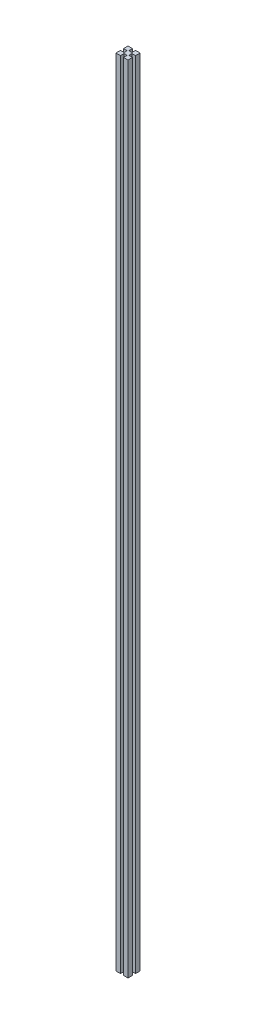
SolidWorks part; units mm, degrees
ref_plane "Front Plane" through (0, 0, 0) normal (0, 0, 1) x (1, 0, 0)
ref_plane "Top Plane" through (0, 0, 0) normal (0, 1, 0) x (1, 0, 0)
ref_plane "Right Plane" through (0, 0, 0) normal (1, 0, 0) x (0, 0, -1)
sketch "Sketch1" plane through (0, 0, 0) normal (0, 1, 0) x (1, 0, 0)
  line L1 (-10, -10) -> (10, -10)
  line L2 (-10, -10) -> (-10, 10)
  line L3 (-10, 10) -> (10, 10)
  line L4 (10, -10) -> (10, 10)
  line L5 (-10, -10) -> (10, 10) construction
  line L6 (-10, 10) -> (10, -10) construction
  point P0 (0, 0)
  dimension "D1" = 20
  dimension "D2" = 20
extrude "Boss-Extrude1" add sketch "Sketch1" along normal blind 656.463 and the other way blind 656.463
sketch "Sketch2" plane through (0, 0, 0) normal (0, 1, 0) x (1, 0, 0)
  line L0 (-2.5, 4) -> (2.5, 4)
  line L1 (-2.5, 4) -> (-2.5, 16)
  line L2 (-2.5, 16) -> (2.5, 16)
  line L3 (2.5, 4) -> (2.5, 16)
  line L4 (-2.5, 4) -> (2.5, 16) construction
  line L5 (-2.5, 16) -> (2.5, 4) construction
  line L6 (4, 2.5) -> (16, 2.5)
  line L7 (4, 2.5) -> (4, -2.5)
  line L8 (4, -2.5) -> (16, -2.5)
  line L9 (16, 2.5) -> (16, -2.5)
  line L10 (4, 2.5) -> (16, -2.5) construction
  line L11 (4, -2.5) -> (16, 2.5) construction
  line L12 (-10, 10) -> (10, -10) construction
  line L13 (-16, 2.5) -> (-4, -2.5) construction
  line L14 (-4, 2.5) -> (-16, -2.5) construction
  line L15 (-4, -2.5) -> (-16, -2.5)
  line L16 (-16, 2.5) -> (-16, -2.5)
  line L17 (-4, 2.5) -> (-16, 2.5)
  line L18 (-4, 2.5) -> (-4, -2.5)
  line L19 (2.5, -4) -> (2.5, -16)
  line L20 (2.5, -4) -> (-2.5, -16) construction
  line L21 (-2.5, -4) -> (2.5, -16) construction
  line L22 (-2.5, -16) -> (2.5, -16)
  line L23 (-2.5, -4) -> (2.5, -4)
  line L24 (-2.5, -4) -> (-2.5, -16)
  line L25 (-10, 10) -> (-10, -10) construction
  line L26 (10, -10) -> (10, 10) construction
  line L27 (-10, -10) -> (10, -10) construction
  line L28 (10, 10) -> (-10, 10) construction
  point P0 (0, 10)
  point P5 (10, 0)
  point P16 (-10, 0)
  point P21 (0, -10)
  dimension "D1" = 5
  dimension "D2" = 12
  dimension "D3" = 5
  dimension "D4" = 12
extrude "Cut-Extrude1" cut sketch "Sketch2" against normal through all both and the other way through all
